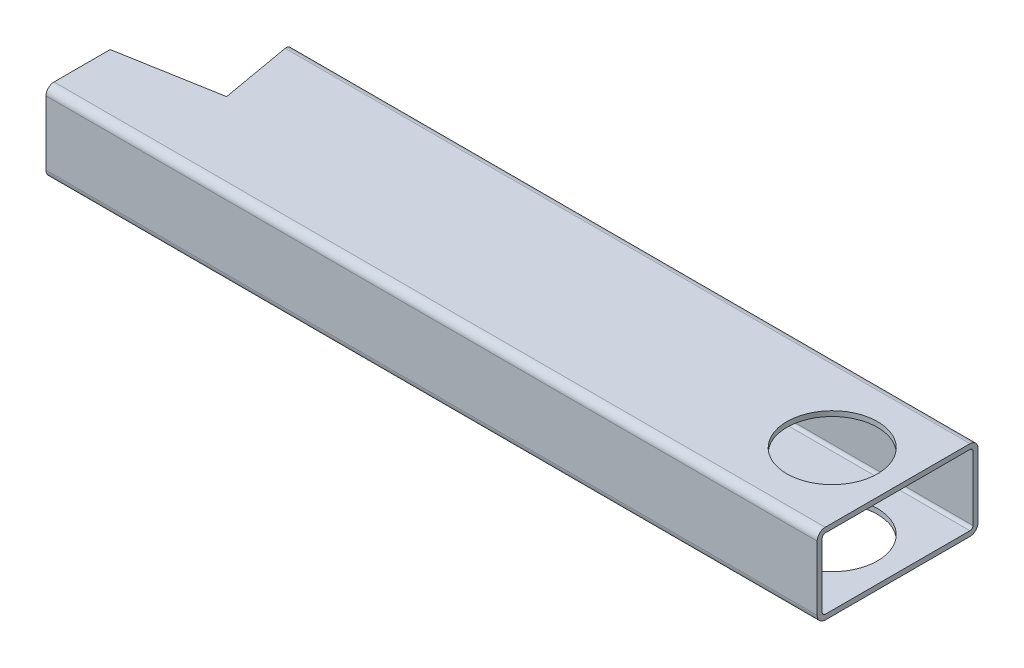
SolidWorks part; units mm, degrees
material "6061 Alloy"
ref_plane "Front" through (0, 0, 0) normal (0, 0, 1) x (1, 0, 0)
ref_plane "Top" through (0, 0, 0) normal (0, 1, 0) x (1, 0, 0)
ref_plane "Right" through (0, 0, 0) normal (1, 0, 0) x (0, 0, -1)
sketch "Sketch1" plane through (0, 0, 0) normal (1, 0, 0) x (0, 0, -1)
  line L1 (-2.54, 0) -> (-48.26, 0)
  line L2 (0, 2.54) -> (0, 22.86)
  line L3 (-2.54, 25.4) -> (-48.26, 25.4)
  line L4 (-50.8, 2.54) -> (-50.8, 22.86)
  arc A0 (-50.8, 2.54) -> (-48.26, 0) centre (-48.26, 2.54) ccw
  arc A1 (-2.54, 0) -> (0, 2.54) centre (-2.54, 2.54) ccw
  arc A2 (0, 22.86) -> (-2.54, 25.4) centre (-2.54, 22.86) ccw
  arc A3 (-48.26, 25.4) -> (-50.8, 22.86) centre (-48.26, 22.86) ccw
  point P7 (-50.8, 0)
  point P10 (0, 0)
  point P13 (0, 25.4)
  dimension "D3" = 2.54
  dimension "D1" = 25.4
  dimension "D2" = 50.8
extrude "Extrude-Thin1" add sketch "Sketch1" against normal blind 243.6368 thin
sketch "Sketch3" plane through (0, 25.4, 0) normal (0, 1, 0) x (1, 0, 0)
  line L0 (0, 49.2125) -> (79.6022, 243.0747)
  line L1 (0, -1.5875) -> (25.4, -1.5875)
  line L2 (0, -1.5875) -> (0, 49.2125)
  line L3 (0, 49.2125) -> (25.4, 49.2125)
  line L4 (25.4, -1.5875) -> (25.4, 49.2125)
  line L5 (79.6022, 243.0747) -> (126.5949, 223.7789)
  line L6 (126.5949, 223.7789) -> (34.0567, -1.5875)
  line L7 (71.7537, 223.9604) -> (118.7463, 204.6646) construction
  line L8 (95.25, 214.3125) -> (0, 214.3125)
  line L9 (0, 49.2125) -> (0, 289.0515)
  line L10 (25.4, -1.5875) -> (34.0567, -1.5875)
  circle A0 centre (95.25, 214.3125) radius 14.3129
  point P11 (95.25, 214.3125)
  dimension "D4" = 28.6258
  dimension "D5" = 6.35
  dimension "D1" = 25.4
  dimension "D2" = 50.8
  dimension "D3" = 50.8
  dimension "D6" = 95.25
  dimension "D7" = 165.1
  dimension "D8" = 243.6254
  dimension "D9" = 209.5687
sketch "Sketch4" plane through (0, 25.4, 0) normal (0, 1, 0) x (1, 0, 0)
  line L0 (-20.6629, -48.26) -> (-20.6629, -2.54) construction
  line L2 (-243.6368, -2.54) -> (0, -2.54) construction
  line L3 (-243.6368, -48.26) -> (0, -48.26) construction
  line L4 (0, -2.54) -> (0, -48.26) construction
  line L5 (0, 0) -> (-216.7798, 0) construction
  line L6 (-243.6368, 0) -> (0, 0) construction
  line L7 (-216.7798, 0) -> (-212.3692, -25.0141)
  line L8 (-212.3692, -25.0141) -> (-243.6368, -30.5274)
  line L11 (-216.7798, 0) -> (-243.6368, 0)
  line L12 (-243.6368, 0) -> (-243.6368, -30.5274)
  circle A0 centre (-20.6629, -25.4) radius 14.3129
  point P5 (-20.6629, -25.4)
  point P12 (0, 0)
  dimension "D1" = 28.6258
  dimension "D2" = 6.35
  dimension "D3" = 25.4
  dimension "D4" = 31.75
  dimension "D5" = 80
extrude "Cut-Extrude1" cut sketch "Sketch4" against normal through all and the other way through all
